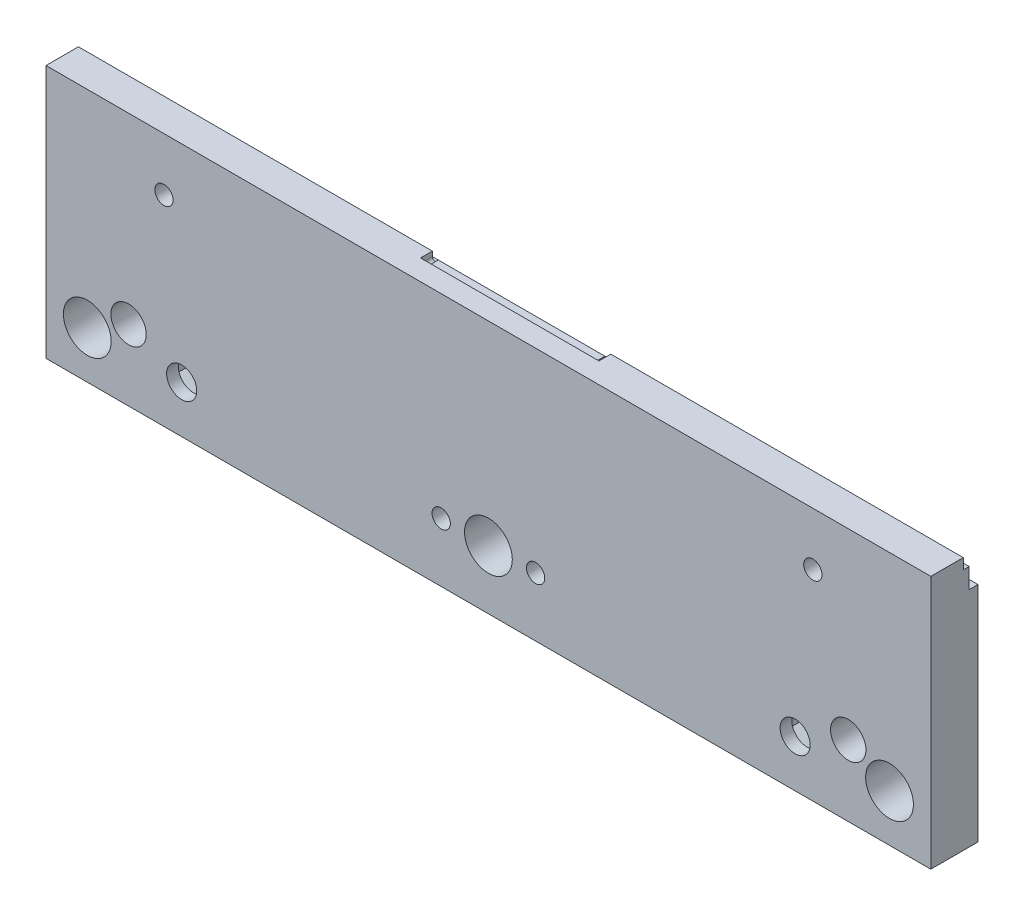
SolidWorks part; units mm, degrees
ref_plane "前视基准面" through (0, 0, 0) normal (0, 0, 1) x (1, 0, 0)
ref_plane "上视基准面" through (0, 0, 0) normal (0, 1, 0) x (1, 0, 0)
ref_plane "右视基准面" through (0, 0, 0) normal (1, 0, 0) x (0, 0, -1)
sketch "草图2" plane through (0, 0, 0) normal (0, 0, 1) x (1, 0, 0)
  line L0 (0, 0) -> (150, 0)
  line L2 (150, 0) -> (150, 43)
  line L3 (150, 43) -> (0, 43)
  line L5 (0, 43) -> (0, 0)
  line L6 (75, 43) -> (75, 0) construction
  circle A0 centre (7, 8) radius 4.05
  circle A1 centre (75, 10) radius 4.05
  circle A2 centre (143, 8) radius 4.05
  dimension "D3" = 8
  dimension "D5" = 10
  dimension "D9" = 8.1
  dimension "D10" = 8.1
  dimension "D11" = 8.1
  dimension "D1" = 43
  dimension "D2" = 150
  dimension "D4" = 7
  dimension "D6" = 7
  dimension "D7" = 8
extrude "凸台-拉伸1" add sketch "草图2" along normal blind 8
sketch "草图3" plane through (0, 0, 8) normal (0, 0, 1) x (1, 0, 0)
  line L0 (16.088, 8) -> (31.4805, 8) construction
  line L1 (7, 8) -> (7, 16.8386) construction
  line L2 (143, 8) -> (143, 16.5917) construction
  circle A2 centre (23, 8) radius 2.55
  circle A3 centre (127, 8) radius 2.55
  dimension "D4" = 5.1
  dimension "D5" = 5.1
  dimension "D1" = 8
  dimension "D2" = 16
  dimension "D3" = 16
extrude "切除-拉伸1" cut sketch "草图3" against normal through all
sketch "草图4" plane through (150, 0, 0) normal (1, 0, 0) x (0, 0, -1)
  line L2 (-1.5, 41.2) -> (-2.5, 41.2)
  line L3 (-2.5, 41.2) -> (-2.5, 43)
  line L4 (-8, 43) -> (0, 43) construction
  line L5 (-2.5, 43) -> (0, 43)
  line L6 (-1.5, 41.2) -> (-1.5, 37.8)
  line L7 (-1.5, 37.8) -> (0, 37.8)
  line L8 (0, 37.8) -> (0, 43)
  dimension "D1" = 3.4
  dimension "D2" = 2.5
  dimension "D3" = 1.5
  dimension "D4" = 1.8
extrude "切除-拉伸2" cut sketch "草图4" against normal through all
sketch "草图5" plane through (0, 0, 8) normal (0, 0, 1) x (1, 0, 0)
  line L0 (75, 10) -> (91.5376, 10) construction
  circle A0 centre (75, 10) radius 8 construction
  circle A1 centre (83, 10) radius 1.55
  circle A2 centre (67, 10) radius 1.55
  dimension "D1" = 3.1
  dimension "D2" = 3.1
  dimension "D3" = 16
extrude "切除-拉伸3" cut sketch "草图5" against normal through all
sketch "草图7" plane through (0, 0, 0) normal (0, 0, -1) x (-1, 0, 0)
  line L0 (-75, 12) -> (-75, -8.3696) construction
  line L1 (-23, 10) -> (-23, -2.3368) construction
  line L6 (-27.05, 10) -> (-27.05, 2.5)
  line L7 (-29.55, 0) -> (-16.45, 0)
  line L8 (-18.95, 2.5) -> (-18.95, 10)
  line L9 (-23, 8) -> (-23, 15.9045) construction
  line L14 (-127, 8) -> (-127, 15.9045) construction
  line L15 (-127, 10) -> (-127, -2.3368) construction
  line L16 (-131.05, 2.5) -> (-131.05, 10)
  line L17 (-120.45, 0) -> (-133.55, 0)
  line L18 (-122.95, 10) -> (-122.95, 2.5)
  line L19 (0, 0) -> (-150, 0) construction
  line L21 (0, 43) -> (-150, 43) construction
  arc A1 (-18.95, 10) -> (-27.05, 10) centre (-23, 10) ccw
  arc A4 (-29.55, 0) -> (-27.05, 2.5) centre (-29.55, 2.5) ccw
  arc A5 (-18.95, 2.5) -> (-16.45, 0) centre (-16.45, 2.5) ccw
  arc A7 (-131.05, 2.5) -> (-133.55, 0) centre (-133.55, 2.5) cw
  arc A8 (-120.45, 0) -> (-122.95, 2.5) centre (-120.45, 2.5) cw
  arc A9 (-131.05, 10) -> (-122.95, 10) centre (-127, 10) cw
  point P11 (-75, 43)
  dimension "D4" = 8.1
  dimension "D7" = 2.5
  dimension "D8" = 2.5
  dimension "D2" = 10
extrude "切除-拉伸4" [suppressed] cut sketch "草图7" against normal blind 6
sketch "草图8" plane through (0, 0, 0) normal (0, 0, -1) x (-1, 0, 0)
  line L0 (-75, 10) -> (-92.3165, 10) construction
  line L1 (-75, 20) -> (-75, 35.6562) construction
  line L2 (-65.5, 12.85) -> (-84.5, 12.85)
  line L3 (-84.5, 7.15) -> (-65.5, 7.15)
  line L5 (-150, 0) -> (-150, 37.8) construction
  line L6 (-83, 6.7091) -> (-80.15, 8.3546)
  line L7 (-80.15, 8.3546) -> (-80.15, 11.6454)
  line L8 (-80.15, 11.6454) -> (-83, 13.2909)
  line L9 (-83, 13.2909) -> (-85.85, 11.6454)
  line L10 (-85.85, 11.6454) -> (-85.85, 8.3546)
  line L11 (-85.85, 8.3546) -> (-83, 6.7091)
  line L12 (-69.85, 11.6454) -> (-69.85, 8.3546)
  line L13 (-69.85, 8.3546) -> (-67, 6.7091)
  line L14 (-67, 6.7091) -> (-64.15, 8.3546)
  line L15 (-64.15, 8.3546) -> (-64.15, 11.6454)
  line L16 (-64.15, 11.6454) -> (-67, 13.2909)
  line L17 (-67, 13.2909) -> (-69.85, 11.6454)
  line L21 (-75, 10) -> (-75, -3.659) construction
  arc A0 (-65.5, 7.15) -> (-65.5, 12.85) centre (-65.5, 10) ccw
  arc A1 (-84.5, 12.85) -> (-84.5, 7.15) centre (-84.5, 10) ccw
  circle A2 centre (-83, 10) radius 2.85 construction
  circle A3 centre (-67, 10) radius 2.85 construction
  dimension "D1" = 5.7
  dimension "D2" = 9.5
  dimension "D3" = 9.5
  dimension "D4" = 10
  dimension "D5" = 5.7
sketch "草图11" plane through (0, 0, 0) normal (0, 0, -1) x (-1, 0, 0)
  line L0 (0, 43) -> (-150, 43) construction
  line L1 (-150, 0) -> (-150, 37.8) construction
  line L3 (-40, 20) -> (-40, 13.5744) construction
  line L4 (-28.772, 34) -> (-45.9396, 34) construction
  line L5 (0, 37.8) -> (0, 0) construction
  circle A0 centre (-130, 34) radius 1.55
  circle A1 centre (-20, 34) radius 1.55
  point P23 (-40, 20)
  dimension "D1" = 3.1
  dimension "D2" = 3.1
  dimension "D3" = 20
  dimension "D4" = 20
  dimension "D5" = 9
sketch "草图20" plane through (0, 0, 0) normal (0, 0, -1) x (-1, 0, 0)
  circle A0 centre (-75, 10) radius 5.5
  dimension "D1" = 11
extrude "切除-拉伸15" cut sketch "草图8" against normal blind 4.5 contours L10 L11 L6 L7 L8 L9 | L13 L14 L15 L16 L17 L12
extrude "切除-拉伸7" cut sketch "草图11" against normal through all contours A0 | A1
sketch "草图19" plane through (0, 0, 2.5) normal (0, 0, -1) x (-1, 0, 0)
  line L0 (0, 43) -> (-150, 43) construction
  line L1 (-60, 43) -> (-90.2479, 43)
  line L2 (-60, 43) -> (-60, 42.2)
  line L3 (-61, 42.2) -> (-89.2479, 42.2)
  line L4 (-90.2479, 43) -> (-90.2479, 42.2)
  line L7 (0, 41.2) -> (-150, 41.2) construction
  line L8 (-56.3335, 41.7) -> (-52.9089, 41.7) construction
  line L9 (-90.2479, 1028.5823) -> (-90.2479, 42.2) construction
  line L10 (-60, 1028.5823) -> (-60, 41.7) construction
  line L11 (-90.2479, 41.7) -> (-90.2479, -973.3) construction
  line L12 (-60, 41.7) -> (-60, -973.3) construction
  arc A3 (-90.2479, 42.2) -> (-89.2479, 42.2) centre (-89.7479, 42.2) ccw
  arc A6 (-61, 42.2) -> (-60, 42.2) centre (-60.5, 42.2) ccw
  dimension "D3" = 1
  dimension "D4" = 1
  dimension "D5" = 15
  dimension "D6" = 30.2479
  dimension "D2" = 0.8
  dimension "D1" = 0.5
extrude "切除-拉伸11" cut sketch "草图19" against normal blind 2
sketch "草图21" plane through (0, 0, 0) normal (0, 0, -1) x (-1, 0, 0)
  line L0 (-150, 12) -> (0, 12) construction
  line L1 (-150, 0) -> (-150, 37.8) construction
  line L3 (-14, 37.8) -> (-14, 0) construction
  line L4 (0, 37.8) -> (-150, 37.8) construction
  line L6 (-75, 37.8) -> (-75, 0) construction
  line L8 (0, 0) -> (-150, 0) construction
  line L9 (0, 37.8) -> (0, 0) construction
  circle A0 centre (-14, 12) radius 3
  circle A1 centre (-136, 12) radius 3
  point P4 (0, 0)
  point P5 (0, 0)
  point P10 (0, 0)
  dimension "D3" = 6
  dimension "D1" = 12
  dimension "D2" = 14
extrude "切除-拉伸13" cut sketch "草图21" against normal through all
sketch "草图22" plane through (0, 0, 0) normal (0, 0, -1) x (-1, 0, 0)
  line L0 (-150, 0) -> (-150, 37.8) construction
  line L1 (-122.9, 5.6329) -> (-122.9, 10.3671)
  line L2 (-122.9, 10.3671) -> (-127, 12.7343)
  line L3 (-127, 12.7343) -> (-131.1, 10.3671)
  line L4 (-131.1, 10.3671) -> (-131.1, 5.6329)
  line L5 (-131.1, 5.6329) -> (-127, 3.2657)
  line L6 (-127, 3.2657) -> (-122.9, 5.6329)
  line L7 (-23, 3.2657) -> (-18.9, 5.6329)
  line L8 (-18.9, 5.6329) -> (-18.9, 10.3671)
  line L9 (-18.9, 10.3671) -> (-23, 12.7343)
  line L10 (-23, 12.7343) -> (-27.1, 10.3671)
  line L11 (-27.1, 10.3671) -> (-27.1, 5.6329)
  line L12 (-27.1, 5.6329) -> (-23, 3.2657)
  circle A0 centre (-127, 8) radius 4.1 construction
  circle A1 centre (-23, 8) radius 4.1 construction
  dimension "D1" = 8.2
extrude "切除-拉伸14" cut sketch "草图22" against normal blind 6
